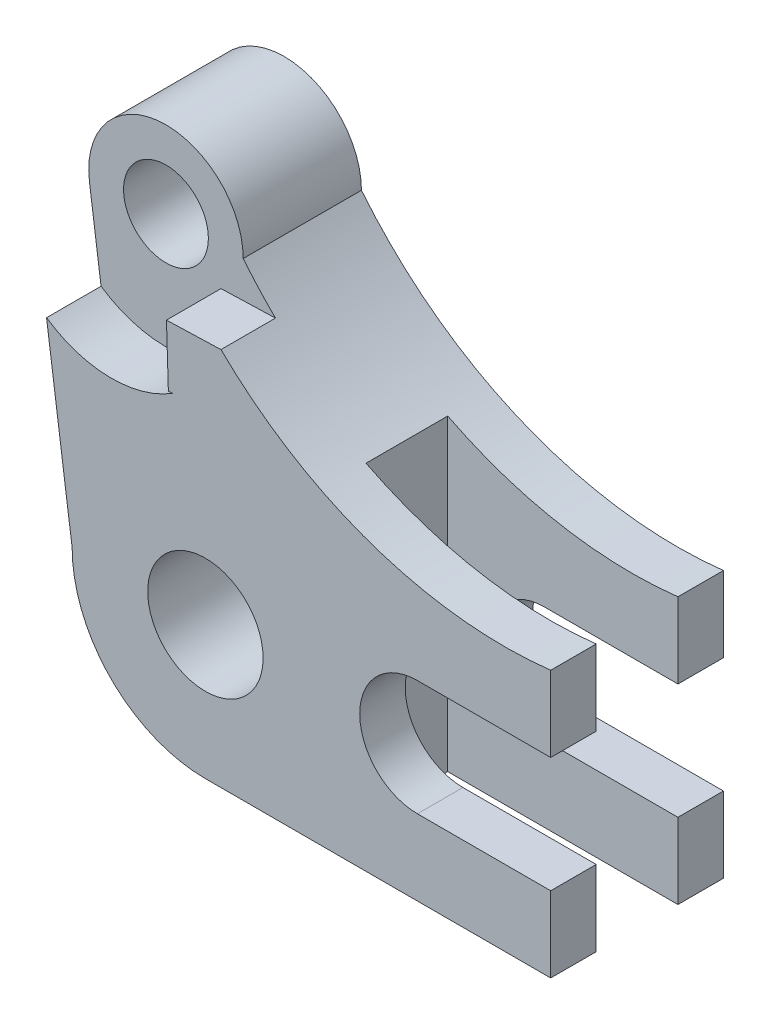
SolidWorks part; units mm, degrees
ref_plane "Front Plane" through (0, 0, 0) normal (0, 0, 1) x (1, 0, 0)
ref_plane "Top Plane" through (0, 0, 0) normal (0, 1, 0) x (1, 0, 0)
ref_plane "Right Plane" through (0, 0, 0) normal (1, 0, 0) x (0, 0, -1)
sketch "Sketch1" plane through (0, 0, 0) normal (0, 0, 1) x (1, 0, 0)
  line L0 (0, 128.4732) -> (0, -36.8792) construction
  line L1 (120.1241, 0) -> (-50.1241, 0) construction
  line L2 (-9.6118, 35.8718) -> (11.0067, -41.0775) construction
  line L3 (-22, 0) -> (-28.144, 44.7452)
  line L4 (-15.5126, 81.6144) -> (-15.5126, 11.345) construction
  line L6 (57, 22) -> (57, 9.525)
  line L7 (57, 9.525) -> (35, 9.525)
  line L9 (35, -9.525) -> (57, -9.525)
  line L10 (57, -9.525) -> (57, -22)
  line L11 (57, -22) -> (0, -22)
  circle A0 centre (0, 0) radius 9.525
  arc A1 (-22, 0) -> (0, -22) centre (0, 0) ccw
  circle A2 centre (-15.5126, 46.4797) radius 7
  arc A3 (-2.7626, 46.4797) -> (-28.144, 44.7452) centre (-15.5126, 46.4797) ccw
  arc A4 (-2.7626, 46.4797) -> (57, 22) centre (49.3708, 88.5642) ccw
  arc A6 (35, 9.525) -> (35, -9.525) centre (35, 0) ccw
  dimension "D1" = 19.05
  dimension "D2" = 22
  dimension "D4" = 49
  dimension "D5" = 25.5
  dimension "D6" = 67
  dimension "D7" = 12.475
  dimension "D10" = 22
  dimension "D12" = 14
  dimension "D8" = 57
  dimension "D3" = 15
  dimension "D9" = 22
  dimension "D11" = 46.4797
extrude "Boss-Extrude1" add sketch "Sketch1" along normal blind 28.52
sketch "Sketch2" plane through (0, 0, 28.52) normal (0, 0, 1) x (1, 0, 0)
  line L0 (-28.144, 44.7452) -> (-22, 0) construction
  line L3 (-28.144, 44.7452) -> (-26.2277, 30.7894)
  line L5 (-2.7626, 46.4797) -> (2.5633, 40.6262)
  arc A0 (-26.2277, 30.7894) -> (2.5633, 40.6262) centre (-15.5126, 46.4797) ccw
  arc A1 (-2.7626, 46.4797) -> (57, 22) centre (49.3708, 88.5642) ccw construction
  arc A3 (-2.7626, 46.4797) -> (-28.144, 44.7452) centre (-15.5126, 46.4797) ccw construction
  arc A5 (-2.7626, 46.4797) -> (-28.144, 44.7452) centre (-15.5126, 46.4797) ccw
  dimension "D1" = 19
extrude "Cut-Extrude10" cut sketch "Sketch2" against normal blind 9
ref_plane "Plane2" through (0, 40, 0) normal (0, 1, 0) x (1, 0, 0)
sketch "Sketch5" plane through (0, 40, 0) normal (0, 1, 0) x (1, 0, 0)
  line L0 (57, -28.52) -> (57, 0) construction
  line L1 (19, -7.515) -> (57, -7.515)
  line L2 (19, -7.515) -> (19, -21.005)
  line L3 (19, -21.005) -> (57, -21.005)
  line L7 (57, -7.515) -> (57, -21.005)
  point P0 (57, -14.26)
  dimension "D1" = 13.49
extrude "Cut-Extrude11" cut sketch "Sketch5" against normal through all
sketch "Sketch8" plane through (0, 0, 28.52) normal (0, 0, 1) x (1, 0, 0)
  line L0 (2.5633, 40.6262) -> (-6.4322, 40.3429)
extrude "Extrude-Thin4" add sketch "Sketch8" against normal blind 9 separate body thin
sketch "Sketch9" plane through (-1.5901, 50.5004, 0) normal (-0.0315, 0.9995, 0) x (0.9995, 0.0315, 0)
  line L0 (-5.1594, -28.52) -> (-5.1594, -19.52)
  line L1 (-5.1594, -19.52) -> (3.8406, -19.52)
  line L2 (3.8406, -19.52) -> (3.8406, -28.52)
  line L3 (3.8406, -19.52) -> (3.8406, -28.52) construction
  line L4 (3.8406, -28.52) -> (-5.1594, -28.52)
  line L5 (3.8406, -28.52) -> (-5.1594, -28.52) construction
extrude "Boss-Extrude3" add sketch "Sketch9" against normal blind 20
sketch "Sketch10" plane through (3.8387, 0.1209, 0) normal (0.9995, 0.0315, 0) x (0, 0, -1)
  line L0 (-28.52, 50.5254) -> (-19.52, 50.5254)
  line L1 (-28.52, 50.5254) -> (-19.52, 50.5254) construction
  line L2 (-19.52, 50.5254) -> (-19.52, 40.5254)
  line L3 (-19.52, 40.5254) -> (-19.52, 50.5254) construction
  line L4 (-19.52, 40.5254) -> (-28.52, 40.5254)
  line L5 (-28.52, 40.5254) -> (-28.52, 50.5254)
extrude "Cut-Extrude12" cut sketch "Sketch10" against normal through all
